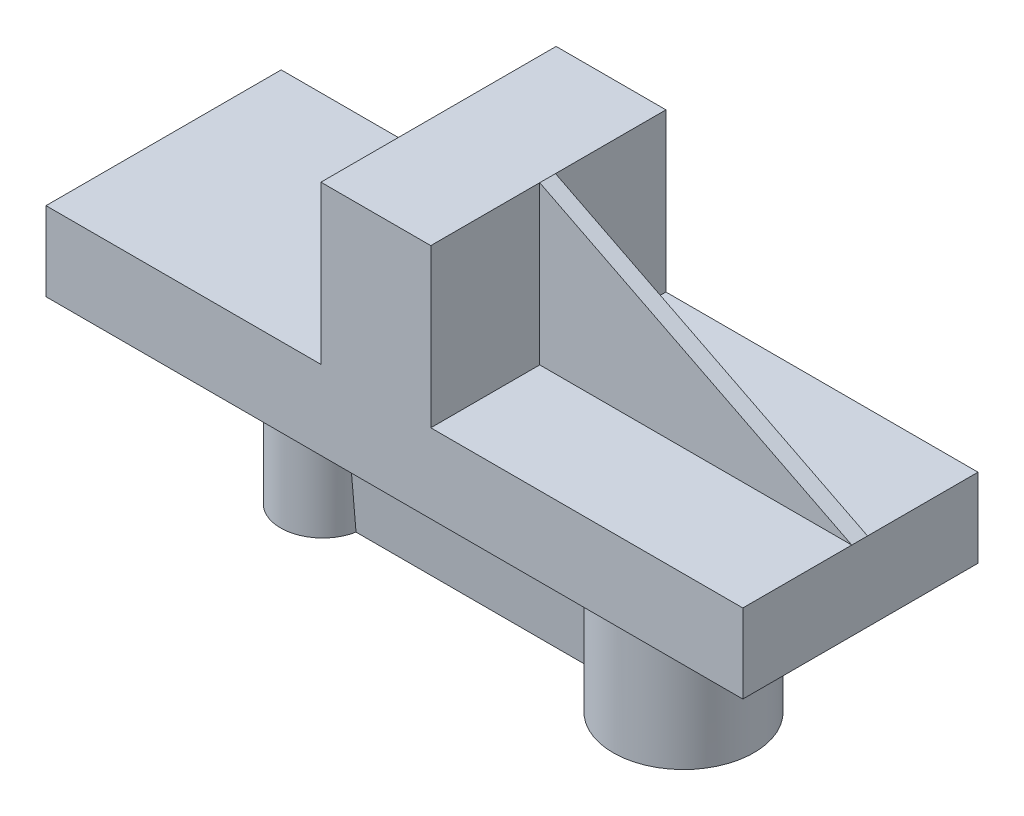
SolidWorks part; units mm, degrees
ref_plane "Front Plane" through (0, 0, 0) normal (0, 0, 1) x (1, 0, 0)
ref_plane "Top Plane" through (0, 0, 0) normal (0, 1, 0) x (1, 0, 0)
ref_plane "Right Plane" through (0, 0, 0) normal (1, 0, 0) x (0, 0, -1)
sketch "Sketch1" plane through (0, 0, 0) normal (0, 1, 0) x (1, 0, 0)
  line L1 (0, 0) -> (88.3233, 0)
  line L2 (0, 0) -> (0, -29.8091)
  line L3 (0, -29.8091) -> (88.3233, -29.8091)
  line L4 (88.3233, 0) -> (88.3233, -29.8091)
extrude "Boss-Extrude1" add sketch "Sketch1" along normal blind 10
sketch "Sketch2" plane through (0, 10, 0) normal (0, 1, 0) x (1, 0, 0)
  line L0 (88.3233, 0) -> (0, 0) construction
  line L1 (34.8476, 0) -> (48.7716, 0)
  line L2 (34.8476, 0) -> (34.8476, -29.8091)
  line L3 (34.8476, -29.8091) -> (48.7716, -29.8091)
  line L4 (48.7716, 0) -> (48.7716, -29.8091)
  line L5 (0, -29.8091) -> (88.3233, -29.8091) construction
extrude "Boss-Extrude2" add sketch "Sketch2" along normal blind 20
ref_plane "Plane1" through (0, 0, 15) normal (0, 0, 1) x (1, 0, 0)
sketch "Sketch4" plane through (0, 0, 15) normal (0, 0, 1) x (1, 0, 0)
  line L0 (48.7716, 30) -> (88.3233, 10)
rib "Rib1" sketch "Sketch4" sketch "Sketch4" thickness 2 extrusion direction parallel to sketch draft on no parameters "D1"=2
sketch "Sketch5" plane through (0, 0, 0) normal (0, -1, 0) x (1, 0, 0)
  line L0 (16.5, 15) -> (-16.5, 15) construction
  circle A0 centre (20.2556, 15) radius 5.3268
  circle A1 centre (65.9979, 15) radius 8.9267
extrude "Boss-Extrude3" add sketch "Sketch5" along normal blind 20
sketch "Sketch6" plane through (0, 0, 15) normal (0, 0, 1) x (1, 0, 0)
  line L0 (25.5824, -20) -> (57.0711, -20)
rib "Rib2" sketch "Sketch6" sketch "Sketch6" thickness 2 extrusion direction parallel to sketch draft on yes draft angle 4 parameters "D1"=2, "D3"=4
